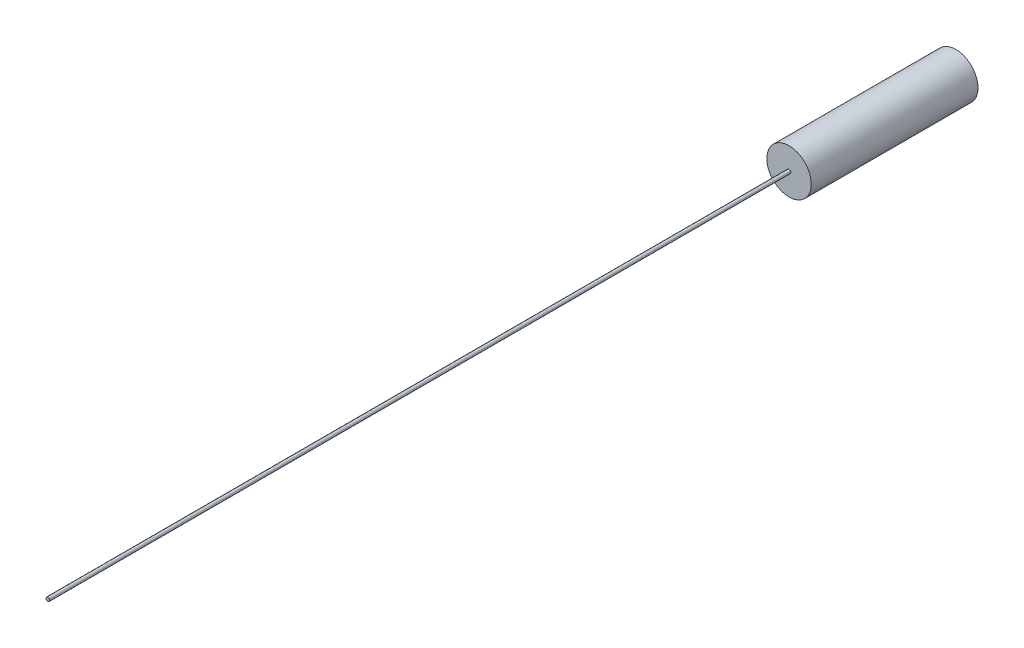
SolidWorks part; units mm, degrees
ref_plane "Front Plane" through (0, 0, 0) normal (0, 0, 1) x (1, 0, 0)
ref_plane "Top Plane" through (0, 0, 0) normal (0, 1, 0) x (1, 0, 0)
ref_plane "Right Plane" through (0, 0, 0) normal (1, 0, 0) x (0, 0, -1)
sketch "Sketch1" plane through (0, 0, 0) normal (0, 0, 1) x (1, 0, 0)
  circle A0 centre (0, 0) radius 6
  dimension "D1" = 12
extrude "Boss-Extrude1" add sketch "Sketch1" along normal blind 45
sketch "Sketch2" plane through (0, 0, 45) normal (0, 0, 1) x (1, 0, 0)
  circle A0 centre (0, 0) radius 0.5
  dimension "D1" = 1
extrude "Boss-Extrude2" add sketch "Sketch2" along normal blind 200
